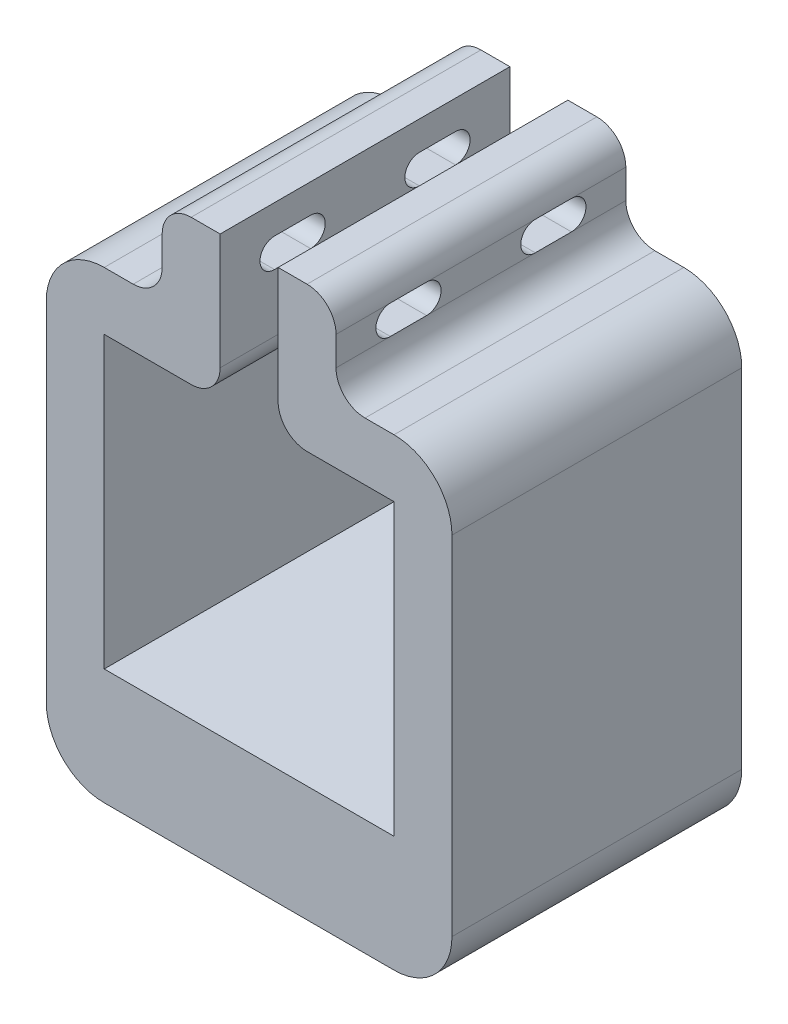
SolidWorks part; units mm, degrees
ref_plane "Front Plane" through (0, 0, 0) normal (0, 0, 1) x (1, 0, 0)
ref_plane "Top Plane" through (0, 0, 0) normal (0, 1, 0) x (1, 0, 0)
ref_plane "Right Plane" through (0, 0, 0) normal (1, 0, 0) x (0, 0, -1)
sketch "Sketch1" plane through (0, 0, 0) normal (0, 0, 1) x (1, 0, 0)
  line L0 (-5.08, 0) -> (-5.08, 25.4)
  line L1 (0, 0) -> (25.4, 0)
  line L2 (0, 0) -> (0, 25.4)
  line L3 (0, 25.4) -> (25.4, 25.4)
  line L4 (25.4, 0) -> (25.4, 25.4)
  line L5 (0, 30.48) -> (25.4, 30.48)
  line L6 (30.48, 0) -> (30.48, 25.4)
  line L7 (0, -5.08) -> (25.4, -5.08)
  line L8 (-5.08, -5.08) -> (30.48, -5.08) construction
  line L9 (30.48, -5.08) -> (30.48, 30.48) construction
  line L10 (-5.08, 30.48) -> (30.48, 30.48) construction
  line L11 (-5.08, -5.08) -> (-5.08, 30.48) construction
  arc A0 (25.4, -5.08) -> (30.48, 0) centre (25.4, 0) ccw
  arc A1 (30.48, 25.4) -> (25.4, 30.48) centre (25.4, 25.4) ccw
  arc A2 (0, 30.48) -> (-5.08, 25.4) centre (0, 25.4) ccw
  arc A3 (0, -5.08) -> (-5.08, 0) centre (0, 0) cw
  dimension "D4" = 5.08
  dimension "D1" = 25.4
  dimension "D2" = 25.4
  dimension "D3" = 5.08
extrude "Boss-Extrude1" add sketch "Sketch1" along normal blind 25.4
sketch "Sketch2" plane through (0, 0, 25.4) normal (0, 0, 1) x (1, 0, 0)
  line L0 (25.4, 30.48) -> (0, 30.48) construction
  line L1 (10.16, 30.48) -> (15.24, 30.48)
  line L2 (10.16, 30.48) -> (10.16, 25.4)
  line L3 (10.16, 25.4) -> (15.24, 25.4)
  line L4 (15.24, 30.48) -> (15.24, 25.4)
  line L5 (25.4, 25.4) -> (0, 25.4) construction
  line L6 (10.16, 25.4) -> (-5.08, 25.4) construction
  line L7 (15.24, 25.4) -> (30.48, 25.4) construction
  dimension "D1" = 5.08
extrude "Cut-Extrude1" cut sketch "Sketch2" against normal through all
fillet "Fillet1" radius 2.54 2 edges at (15.24, 25.4, 12.7) (10.16, 25.4, 12.7)
sketch "Sketch3" plane through (0, 0, 25.4) normal (0, 0, 1) x (1, 0, 0)
  line L1 (10.16, 30.48) -> (5.08, 30.48)
  line L2 (10.16, 30.48) -> (10.16, 38.1)
  line L3 (10.16, 38.1) -> (5.08, 38.1)
  line L4 (5.08, 30.48) -> (5.08, 38.1)
  line L5 (15.24, 30.48) -> (20.32, 30.48)
  line L6 (15.24, 30.48) -> (15.24, 38.1)
  line L7 (15.24, 38.1) -> (20.32, 38.1)
  line L8 (20.32, 30.48) -> (20.32, 38.1)
  dimension "D1" = 5.08
  dimension "D2" = 5.08
  dimension "D3" = 7.62
extrude "Boss-Extrude2" add sketch "Sketch3" against normal up to surface (25.4 mm away) up to face at (12.7, 17.7215, 0)
fillet "Fillet2" radius 2.54 4 edges at (20.32, 30.48, 12.7) (5.08, 30.48, 12.7) (20.32, 38.1, 12.7) (5.08, 38.1, 12.7)
sketch "Sketch4" plane through (5.08, 0, 0) normal (-1, 0, 0) x (0, 0, 1)
  line L0 (4.7625, 34.29) -> (7.9375, 34.29) construction
  line L1 (4.7625, 35.56) -> (7.9375, 35.56)
  line L2 (4.7625, 33.02) -> (7.9375, 33.02)
  line L3 (17.4625, 34.29) -> (20.6375, 34.29) construction
  line L4 (17.4625, 35.56) -> (20.6375, 35.56)
  line L5 (17.4625, 33.02) -> (20.6375, 33.02)
  line L6 (25.4, 35.56) -> (25.4, 33.02) construction
  line L9 (7.9375, 34.29) -> (17.4625, 34.29) construction
  line L10 (20.6375, 34.29) -> (25.4, 34.29) construction
  line L11 (4.7625, 34.29) -> (0, 34.29) construction
  line L12 (0, 33.02) -> (0, 35.56) construction
  arc A0 (4.7625, 35.56) -> (4.7625, 33.02) centre (4.7625, 34.29) ccw
  arc A1 (7.9375, 33.02) -> (7.9375, 35.56) centre (7.9375, 34.29) ccw
  arc A2 (17.4625, 35.56) -> (17.4625, 33.02) centre (17.4625, 34.29) ccw
  arc A3 (20.6375, 33.02) -> (20.6375, 35.56) centre (20.6375, 34.29) ccw
  point P2 (6.35, 34.29)
  point P9 (19.05, 34.29)
  point P14 (21.59, 34.29)
  point P33 (4.445, 59.6265)
  dimension "D5" = 1.27
  dimension "D1" = 3.175
  dimension "D2" = 3.175
  dimension "D4" = 4.7625
extrude "Cut-Extrude2" cut sketch "Sketch4" against normal through all
sketch "Sketch5" plane through (0, -5.08, 0) normal (0, -1, 0) x (1, 0, 0)
  line L1 (-5.08, 25.4) -> (30.48, 25.4)
  line L2 (-5.08, 25.4) -> (-5.08, 0)
  line L3 (-5.08, 0) -> (30.48, 0)
  line L4 (30.48, 25.4) -> (30.48, 0)
extrude "Boss-Extrude3" add sketch "Sketch5" along normal blind 5.08 and the other way up to next (5.08 mm away)
fillet "Fillet3" radius 5.08 2 edges at (30.48, -10.16, 12.7) (-5.08, -10.16, 12.7)
